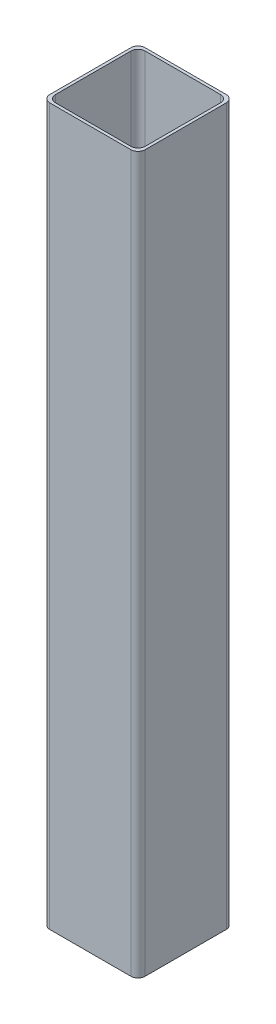
SolidWorks part; units mm, degrees
ref_plane "Plano frontal" through (0, 0, 0) normal (0, 0, 1) x (1, 0, 0)
ref_plane "Plano superior" through (0, 0, 0) normal (0, 1, 0) x (1, 0, 0)
ref_plane "Plano direito" through (0, 0, 0) normal (1, 0, 0) x (0, 0, -1)
sketch "Esboço1" plane through (0, 0, 0) normal (0, 1, 0) x (1, 0, 0)
  line L0 (-18.8, -18.8) -> (-18.8, 18.8)
  line L1 (20, -20) -> (-20, -20)
  line L2 (20, -20) -> (20, 20)
  line L3 (20, 20) -> (-20, 20)
  line L4 (-20, -20) -> (-20, 20)
  line L5 (20, -20) -> (-20, 20) construction
  line L6 (20, 20) -> (-20, -20) construction
  line L7 (18.8, 18.8) -> (-18.8, 18.8)
  line L8 (18.8, -18.8) -> (18.8, 18.8)
  line L9 (18.8, -18.8) -> (-18.8, -18.8)
  point P0 (0, 0)
  dimension "D1" = 40
  dimension "D2" = 40
  dimension "D3" = 1.2
extrude "Ressalto-extrusão1" add sketch "Esboço1" along normal mid plane 300
fillet "Filete1" radius 3 8 edges at (-20, 0, -20) (20, 0, -20) (18.8, 0, -18.8) (18.8, 0, 18.8) (-18.8, 0, 18.8) (-18.8, 0, -18.8) (-20, 0, 20) (20, 0, 20)
